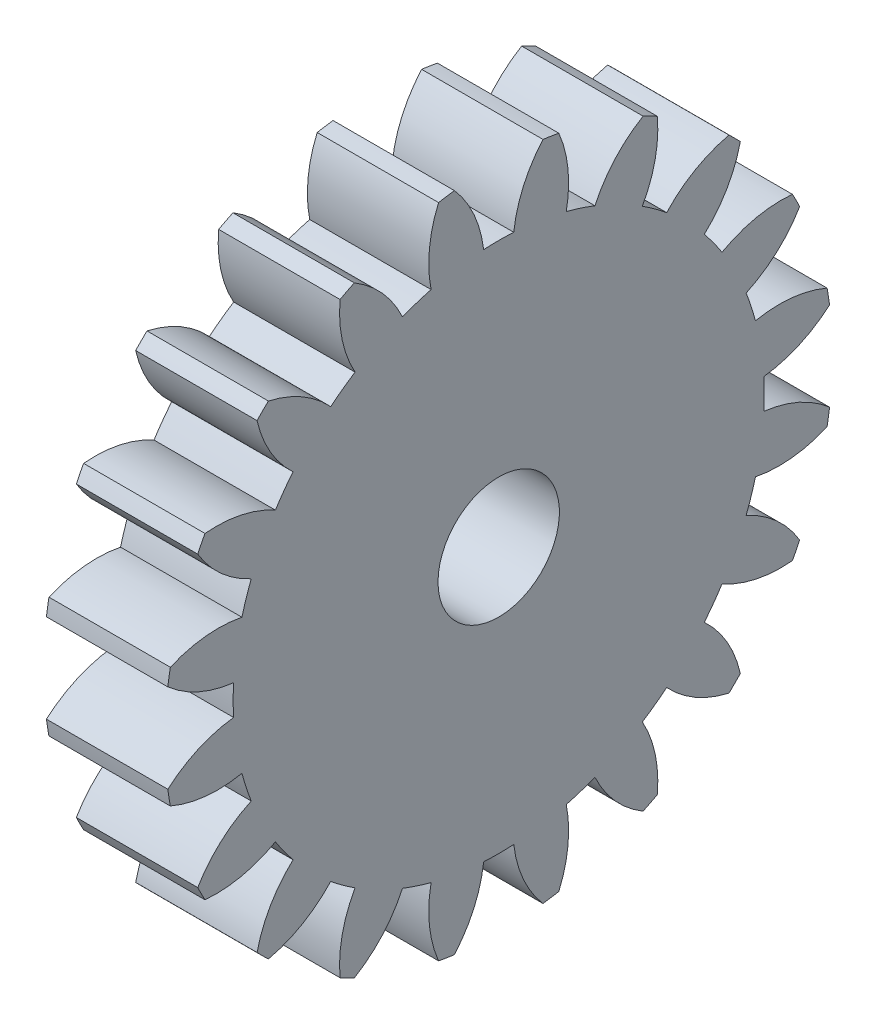
SolidWorks part; units mm, degrees
ref_plane "Plane1" through (0, 0, 0) normal (0, 0, 1) x (1, 0, 0)
ref_plane "Plane2" through (0, 0, 0) normal (0, 1, 0) x (1, 0, 0)
ref_plane "Plane3" through (0, 0, 0) normal (1, 0, 0) x (0, 0, -1)
sketch "HoldingSke" plane through (0, 0, 0) normal (0, 1, 0) x (1, 0, 0)
  line L0 (0, 0) -> (0.6265, -0.228)
  line L1 (-15, 0) -> (100, 0) construction
  line L2 (0, 0) -> (-2.1039, 2.3779)
  line L3 (0, 0) -> (-11.863, 4.5341)
  line L4 (0, 0) -> (8.1152, 2.9537)
  line L5 (0, 0) -> (-46.8476, -17.4728)
  line L6 (0, 0) -> (-4.9738, -3.3558)
  line L7 (-2.1039, 2.3779) -> (8.6586, 51.2059)
  line L8 (-76.2, 54.61) -> (-75.2, 54.61)
  line L9 (-71.009, 38.7566) -> (-53.1078, 45.2721)
  line L10 (-76.2, 71.12) -> (104.1128, 71.12)
  line L11 (0, 0) -> (-6, 0)
  line L12 (-76.2, 101.6) -> (-76.147, 101.6)
  line L13 (24.9733, 27.94) -> (52.9518, 28.4284)
  line L14 (24.9733, 27.94) -> (24.9743, 27.94)
  line L15 (24.9733, 27.94) -> (100.4006, 29.5858)
  line L16 (-63.627, -1.5) -> (-12.827, -1.5)
  circle A0 centre (0, 0) radius 3
  circle A1 centre (0, 0) radius 13.124
  circle A2 centre (0, 0) radius 37.5
  circle A3 centre (0, 0) radius 3
  dimension "Hub_dia" = 75
  dimension "Bore" = 6
  dimension "MBD" = 6
  dimension "Pitch" = 0.6667
  dimension "Overall_len" = 50
  dimension "Thickness" = 6
  dimension "OAL" = 50.0001
  dimension "T_dim" = 1
  dimension "Ap" = 20
  dimension "H" = 19.05
  dimension "Pitch_radius" = 180.3128
  dimension "Width" = 6
  dimension "Backlash" = 0.053
  dimension "Addendum_fac" = 1
  dimension "Dedendum_fac" = 1.25
  dimension "Clearance_fac" = 0.25
  dimension "Dedendum_add" = 0.001
  dimension "Module" = 1.5
sketch "BasProSke" plane through (0, 0, 0) normal (0, 1, 0) x (1, 0, 0)
  line L0 (-10, 0) -> (60, 0) construction
  line L1 (0, 0) -> (0, 16.5)
  line L2 (0, 0) -> (6, 0)
  line L3 (6, 0) -> (6, 16.5)
  line L4 (6, 16.5) -> (0, 16.5)
  dimension "Thickness" = 6
revolve "Base-Revolve" add sketch "BasProSke" angle 360 about L0
sketch "TooCutSke" plane through (0, 0, 0) normal (1, 0, 0) x (0, 0, -1)
  line L1 (0, 0) -> (0, 107) construction
  line L2 (0, 0) -> (-1.2696, 14.9462) construction
  line L3 (0, 0) -> (-4.6808, 29.5532) construction
  line L4 (-1.2696, 14.9462) -> (-2.3404, 14.7766) construction
  arc A0 (0.7438, 13.1029) -> (-0.7438, 13.1029) centre (0, 0) ccw
  arc A1 (2.21, 16.377) -> (-2.21, 16.377) centre (0, 0) ccw
  circle A2 centre (0, 0) radius 15 construction
  circle A3 centre (0, 0) radius 14.0954 construction
  arc A4 (-0.7438, 13.1029) -> (-2.21, 16.377) centre (-6.7025, 12.3999) ccw
  arc A5 (2.21, 16.377) -> (0.7438, 13.1029) centre (6.7025, 12.3999) ccw
  dimension "Half_CT" = 1.0841
extrude "ToothCut" cut sketch "TooCutSke" along normal through all
fillet "Breaks" [suppressed] radius 0.03
fillet "RootFillets" [suppressed] radius 0.376
pattern_circular "TeethCuts" count 20 every 18 about axis through (-10, 0, 0) along (1, 0, 0) of "ToothCut", "RootFillets", "Breaks"
sketch "HubNeaOneSke" plane through (0, 0, 0) normal (-1, 0, 0) x (0, 0, 1)
  circle A0 centre (0, 0) radius 13.124
extrude "HubNearOne" [suppressed] add sketch "HubNeaOneSke" along normal blind 44.0001
sketch "HubNeaBotSke" plane through (0, 0, 0) normal (-1, 0, 0) x (0, 0, 1)
  circle A0 centre (0, 0) radius 13.124
extrude "HubNearBoth" [suppressed] add sketch "HubNeaBotSke" along normal blind 22
ref_plane "FarPln" through (6, 0, 0) normal (1, 0, 0) x (0, 0, -1)
sketch "HubFarSke" plane through (6, 0, 0) normal (1, 0, 0) x (0, 0, -1)
  circle A0 centre (0, 0) radius 13.124
extrude "HubFar" [suppressed] add sketch "HubFarSke" along normal blind 22
sketch "BorSke" plane through (0, 0, 0) normal (1, 0, 0) x (0, 0, -1)
  circle A0 centre (0, 0) radius 3
  dimension "Diameter" = 6
extrude "Bore" cut sketch "BorSke" along normal mid plane 100.0001
sketch "KeySke" plane through (0, 0, 0) normal (1, 0, 0) x (0, 0, -1)
  line L0 (-1, 0) -> (-1, 4)
  line L1 (-1, 4) -> (1, 4)
  line L2 (1, 4) -> (1, 0)
  line L3 (0, 0) -> (0, 34) construction
  line L4 (-1, 0) -> (1, 0)
  dimension "Offset" = 4
  dimension "Width" = 2
extrude "Keyway" [suppressed] cut sketch "KeySke" along normal mid plane 100.0001
pattern_circular "Keyway2" [suppressed] count 2 every 90 about axis through (-10, 0, 0) along (1, 0, 0)
equation "' \"Module@HoldingSke\" = 6.35"
equation "' \"Num_teeth@HoldingSke\" = 12"
equation "' \"Ap@HoldingSke\" =  20"
equation "' \"Ap@HoldingSke\" = 20"
equation "' \"Width@HoldingSke\" = 0.5 * 25.4"
equation "' \"Hub_dia@HoldingSke\"= 1 * 25.4"
equation "' \"Hub_dia@HoldingSke\" = 1 * 25.4"
equation "' \"Overall_len@HoldingSke\" = 1.0 * 25.4"
equation "' \"Bore@HoldingSke\" = 0.75 * 25.4"
equation "' \"T_dim@HoldingSke\" = 0.1 * 25.4"
equation "' \"Width@KeySke\" = 0.25 * 25.4"
equation "' \"Show_teeth@HoldingSke\" = 13"
equation "' \"Backlash@HoldingSke\" = 0.009 * 25.4"
equation "' \"Addendum_fac@HoldingSke\" = 1.0"
equation "' \"Dedendum_fac@HoldingSke\" = 1.25"
equation "' \"Dedendum_add@HoldingSke\" = 0.00005 * 25.4"
equation "' \"Clearance_fac@HoldingSke\" = 0.25"
equation "\"Pitch@HoldingSke\" = 1 / \"Module@HoldingSke\""
equation "\"Overcut_dia@TooCutSke\" = (\"Num_teeth@HoldingSke\" + 2 * \"Addendum_fac@HoldingSke\") / \"Pitch@HoldingSke\" + 0.002 * 25.4"
equation "\"Pitch_dia@TooCutSke\" = \"Num_teeth@HoldingSke\" / \"Pitch@HoldingSke\""
equation "\"Base_dia@TooCutSke\" = \"Num_teeth@HoldingSke\" / \"Pitch@HoldingSke\" * cos((\"Ap@HoldingSke\"  * 3.14159265 / 180))"
equation "\"Root_dia@TooCutSke\" = (\"Num_teeth@HoldingSke\" + 2) / \"Pitch@HoldingSke\" - 2 * (\"Addendum_fac@HoldingSke\" + \"Dedendum_fac@HoldingSke\") / \"Pitch@HoldingSke\" - \"Dedendum_add@HoldingSke\" * 2"
equation "\"Half_ang@TooCutSke\" = 180 / \"Num_teeth@HoldingSke\""
equation "\"Half_CT@TooCutSke\" = \"Num_teeth@HoldingSke\" / \"Pitch@HoldingSke\" * sin((3.14159265 / 2 / \"Num_teeth@HoldingSke\")) / 2 - 7 * \"Backlash@HoldingSke\" / 4"
equation "\"Flank_rad@TooCutSke\" = \"Num_teeth@HoldingSke\" / \"Pitch@HoldingSke\" / 5"
equation "\"Radius@RootFillets\" = \"Clearance_fac@HoldingSke\" / \"Pitch@HoldingSke\" + \"Dedendum_add@HoldingSke\""
equation "\"Break_rad@Breaks\" = 0.02 / \"Pitch@HoldingSke\""
equation "\"Thickness@HoldingSke\" = \"Width@HoldingSke\""
equation "\"OAL@HoldingSke\" = \"Thickness@HoldingSke\""
equation "\"MHD@HoldingSke\" = (\"Num_teeth@HoldingSke\" + 2) / \"Pitch@HoldingSke\" - 2 * (\"Addendum_fac@HoldingSke\" + \"Dedendum_fac@HoldingSke\")  / \"Pitch@HoldingSke\" - \"Dedendum_add@HoldingSke\" * 2"
equation "\"MBD@HoldingSke\" = (\"Num_teeth@HoldingSke\" + 2) / \"Pitch@HoldingSke\" - 2 * (\"Addendum_fac@HoldingSke\" + \"Dedendum_fac@HoldingSke\")  / \"Pitch@HoldingSke\" - \"Dedendum_add@HoldingSke\" * 2 - 0.002 * 25.4"
equation "\"MHD@HoldingSke\" = ((sgn( \"MHD@HoldingSke\" - \"Hub_dia@HoldingSke\" )-1)*( \"MHD@HoldingSke\" - \"Hub_dia@HoldingSke\" ))/-2+ \"Hub_dia@HoldingSke\""
equation "\"MBD@HoldingSke\" = ((sgn( \"MBD@HoldingSke\" - \"Bore@HoldingSke\" )-1)*( \"MBD@HoldingSke\" - \"Bore@HoldingSke\" ))/-2+ \"Bore@HoldingSke\""
equation "\"OAL@HoldingSke\" = ((sgn( \"OAL@HoldingSke\" - \"Overall_len@HoldingSke\" )+1)*( \"OAL@HoldingSke\" - \"Overall_len@HoldingSke\" ))/2 + \"Overall_len@HoldingSke\" + 0.000002 * 25.4"
equation "\"Num_teeth@TeethCuts\" = int( \"Show_teeth@HoldingSke\" ) + 1"
equation "\"Num_teeth@TeethCuts\" = ((sgn( \"Num_teeth@TeethCuts\" - \"Num_teeth@HoldingSke\" )-1)*( \"Num_teeth@TeethCuts\" - \"Num_teeth@HoldingSke\" ))/-2+ \"Num_teeth@HoldingSke\""
equation "\"Num_teeth@TeethCuts\" = ((sgn( \"Num_teeth@TeethCuts\" - 2.0)+1)*( \"Num_teeth@TeethCuts\" - 2.0))/2 +2.0"
equation "\"Angle@TeethCuts\" = 360.0 / \"Num_teeth@HoldingSke\""
equation "\"Diameter@BasProSke\" = (\"Num_teeth@HoldingSke\" + 2 * \"Addendum_fac@HoldingSke\") / \"Pitch@HoldingSke\""
equation "\"Thickness@BasProSke\"  = \"Thickness@HoldingSke\""
equation "' \"Fillet_rad@BasProSke\" =  \"Thickness@HoldingSke\" * 0.05"
equation "' \"Fillet_rad@BasProSke\" = \"Thickness@HoldingSke\" * 0.05"
equation "\"MHD@HoldingSke\" = ((sgn( \"MHD@HoldingSke\" - \"Root_dia@TooCutSke\" )-1)*( \"MHD@HoldingSke\" - \"Root_dia@TooCutSke\" ))/-2+ \"Root_dia@TooCutSke\""
equation "\"Diameter@HubNeaOneSke\" = \"MHD@HoldingSke\""
equation "\"Length@HubNearOne\" = \"OAL@HoldingSke\" - \"Thickness@BasProSke\""
equation "\"Diameter@HubNeaBotSke\" = \"MHD@HoldingSke\""
equation "\"Length@HubNearBoth\" = ( \"OAL@HoldingSke\" - \"Thickness@BasProSke\" ) / 2.0"
equation "\"Thickness@FarPln\" = \"Thickness@BasProSke\""
equation "\"Diameter@HubFarSke\" = \"MHD@HoldingSke\""
equation "\"Length@HubFar\" = ( \"OAL@HoldingSke\" - \"Thickness@BasProSke\" ) / 2.0"
equation "\"Diameter@BorSke\" = \"MBD@HoldingSke\""
equation "\"D1@Bore\" = \"OAL@HoldingSke\" * 2.0"
equation "\"D1@Keyway\" = \"OAL@HoldingSke\" * 2.0"
equation "\"Offset@KeySke\" = \"T_dim@HoldingSke\" + \"MBD@HoldingSke\" / 2.0"
